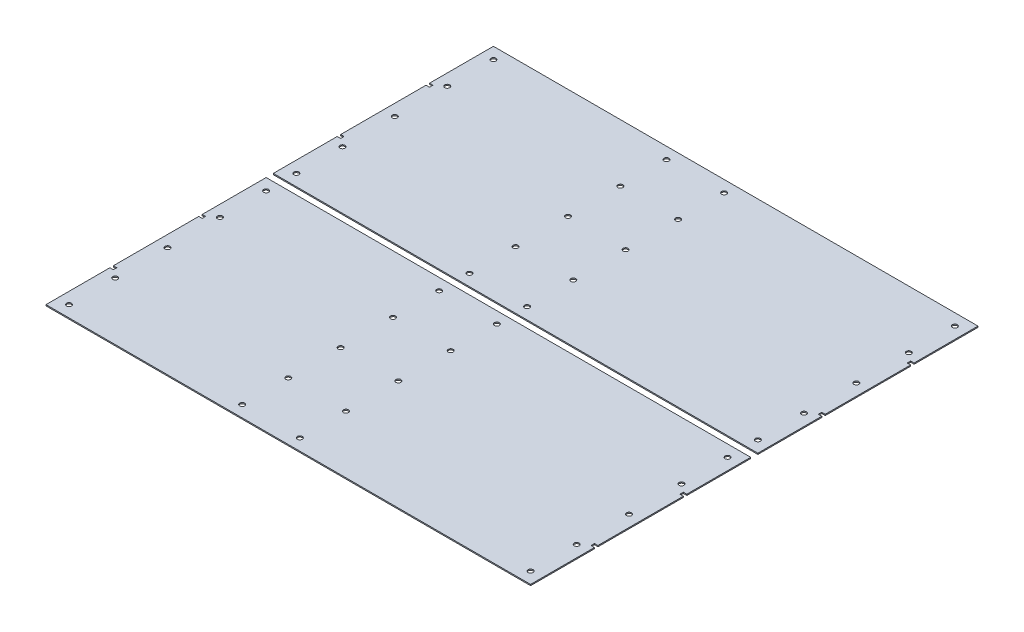
SolidWorks part; units mm, degrees
ref_plane "Front Plane" through (0, 0, 0) normal (0, 0, 1) x (1, 0, 0)
ref_plane "Top Plane" through (0, 0, 0) normal (0, 1, 0) x (1, 0, 0)
ref_plane "Right Plane" through (0, 0, 0) normal (1, 0, 0) x (0, 0, -1)
sketch "Sketch1" plane through (0, 0, 0) normal (0, 1, 0) x (1, 0, 0)
  line L0 (-10, -40) -> (-10, -95.4)
  line L1 (-10, -95.4) -> (410, -95.4)
  line L2 (410, -95.4) -> (410, -40)
  line L3 (410, -40) -> (-10, -40) construction
  line L4 (0, 0) -> (-7, 0) construction
  line L5 (-10, -40) -> (-7, -40)
  line L7 (-7, 40) -> (-10, 40)
  line L8 (-10, 40) -> (-10, 95.4)
  line L9 (-10, 95.4) -> (410, 95.4)
  line L10 (410, 95.4) -> (410, 40)
  line L11 (410, 40) -> (407, 40)
  line L13 (407, -40) -> (410, -40)
  line L14 (0, 45.4) -> (400, 45.4) construction
  line L15 (-7, 40) -> (-7, 37)
  line L16 (-7, 40) -> (407, 40) construction
  line L17 (407, 40) -> (407, -40) construction
  line L18 (-7, 40) -> (-7, -40) construction
  line L19 (-7, 37) -> (-10, 37)
  line L20 (-10, 37) -> (-10, -37)
  line L21 (-10, -37) -> (-7, -37)
  line L22 (-7, -37) -> (-7, -40)
  line L23 (407, 40) -> (407, 37)
  line L24 (407, 37) -> (410, 37)
  line L25 (410, 37) -> (410, -37)
  line L26 (410, -37) -> (407, -37)
  line L27 (407, -37) -> (407, -40)
  line L28 (410, 0) -> (407, 0) construction
  line L29 (400, 45.4) -> (400, -45.4) construction
  line L30 (-7, 0) -> (-10, 0) construction
  line L31 (0, 45.4) -> (0, -45.4) construction
  line L32 (400, -45.4) -> (0, -45.4) construction
  line L33 (0, 45.4) -> (0, 85.4) construction
  line L34 (0, 85.4) -> (400, 85.4) construction
  line L35 (400, 85.4) -> (400, 45.4) construction
  line L36 (400, -45.4) -> (400, -85.4) construction
  line L37 (400, -85.4) -> (0, -85.4) construction
  line L38 (0, -85.4) -> (0, -45.4) construction
  line L39 (0, 0) -> (400, 0) construction
  line L40 (200, 85.4) -> (200, 45.4) construction
  line L41 (200, 45.4) -> (200, 0) construction
  line L42 (200, 0) -> (200, -45.4) construction
  line L43 (200, -45.4) -> (200, -85.4) construction
  line L44 (150, 85.4) -> (150, -85.4) construction
  circle A0 centre (0, -45.4) radius 2.15
  circle A30 centre (0, 45.4) radius 2.15
  circle A31 centre (0, -85.4) radius 2.15
  circle A32 centre (0, 85.4) radius 2.15
  circle A33 centre (200, -85.4) radius 2.15
  circle A34 centre (200, -45.4) radius 2.15
  circle A35 centre (200, 45.4) radius 2.15
  circle A36 centre (200, 85.4) radius 2.15
  circle A53 centre (0, 0) radius 2.15
  circle A54 centre (400, 0) radius 2.15
  circle A55 centre (200, 0) radius 2.15
  circle A59 centre (400, 85.4) radius 2.15
  circle A60 centre (400, 45.4) radius 2.15
  circle A61 centre (400, -45.4) radius 2.15
  circle A62 centre (400, -85.4) radius 2.15
  circle A63 centre (150, 85.4) radius 2.15
  circle A64 centre (150, 45.4) radius 2.15
  circle A65 centre (150, -85.4) radius 2.15
  circle A66 centre (150, -45.4) radius 2.15
  circle A67 centre (150, 0) radius 2.15
  point P17 (0, 65.4)
  point P52 (321.908, -47)
  point P53 (324.3559, 47)
  point P54 (327.3477, 0)
  dimension "D1" = 3
  dimension "D12" = 4.3
  dimension "D9" = 2
  dimension "D11" = 50
  dimension "D3" = 5.4
  dimension "D4" = 10
  dimension "D5" = 10
  dimension "D6" = 40
  dimension "D7" = 10
  dimension "D8" = 3
  dimension "D2" = 74
  dimension "D10" = 420
  dimension "D15" = 200
  dimension "D14" = 2
extrude "Boss-Extrude1" add sketch "Sketch1" along normal blind 1
pattern_linear "LPattern2" count 2 spacing 197 along (0, 0, -1) of bodies 101
